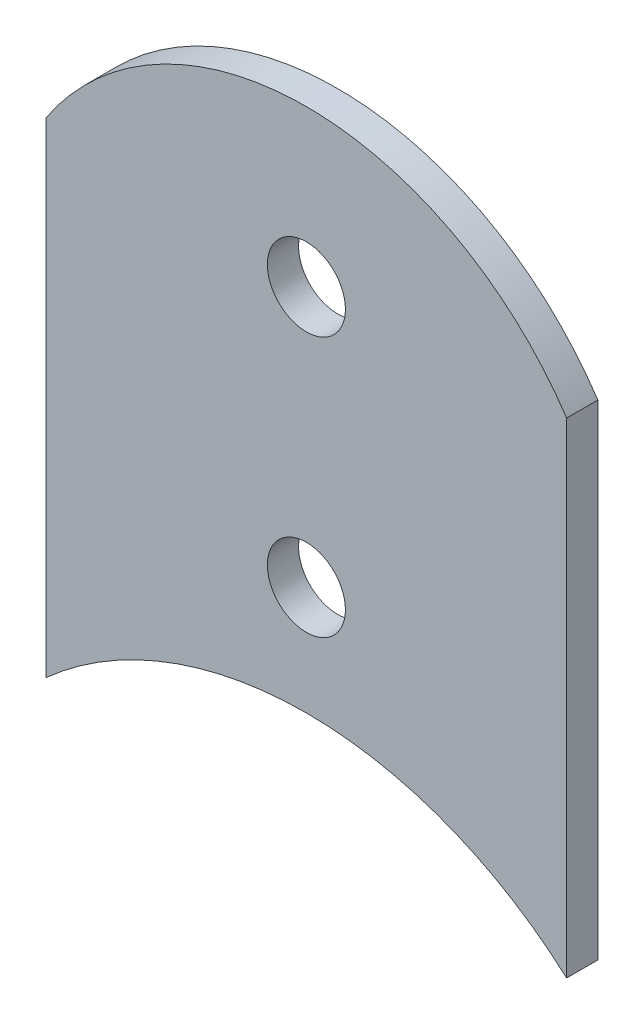
SolidWorks part; units mm, degrees
ref_plane "Ebene vorne" through (0, 0, 0) normal (0, 0, 1) x (1, 0, 0)
ref_plane "Ebene oben" through (0, 0, 0) normal (0, 1, 0) x (1, 0, 0)
ref_plane "Ebene rechts" through (0, 0, 0) normal (1, 0, 0) x (0, 0, -1)
sketch "Skizze1" plane through (0, 0, 0) normal (0, 0, 1) x (1, 0, 0)
  line L0 (0, 0) -> (0, -179.3866) construction
  line L2 (-50, -123.4849) -> (-50, -30.3186)
  line L3 (50, -123.4849) -> (50, -30.3186)
  arc A0 (50, -123.4849) -> (-50, -123.4849) centre (0, -179.3866) ccw
  arc A1 (50, -30.3186) -> (-50, -30.3186) centre (0, -63.4849) ccw
  circle A2 centre (0, -83.4849) radius 7.5
  circle A3 centre (0, -33.4849) radius 7.5
  point P4 (0, -3.4849)
  point P13 (0, 0)
  point P14 (0, 0)
  dimension "D1" = 75
  dimension "D2" = 60
  dimension "D5" = 15
  dimension "D6" = 15
  dimension "D4" = 120
  dimension "D3" = 100
  dimension "D7" = 40
  dimension "D8" = 50
extrude "Aufsatz-Linear austragen1" add sketch "Skizze1" along normal blind 6
